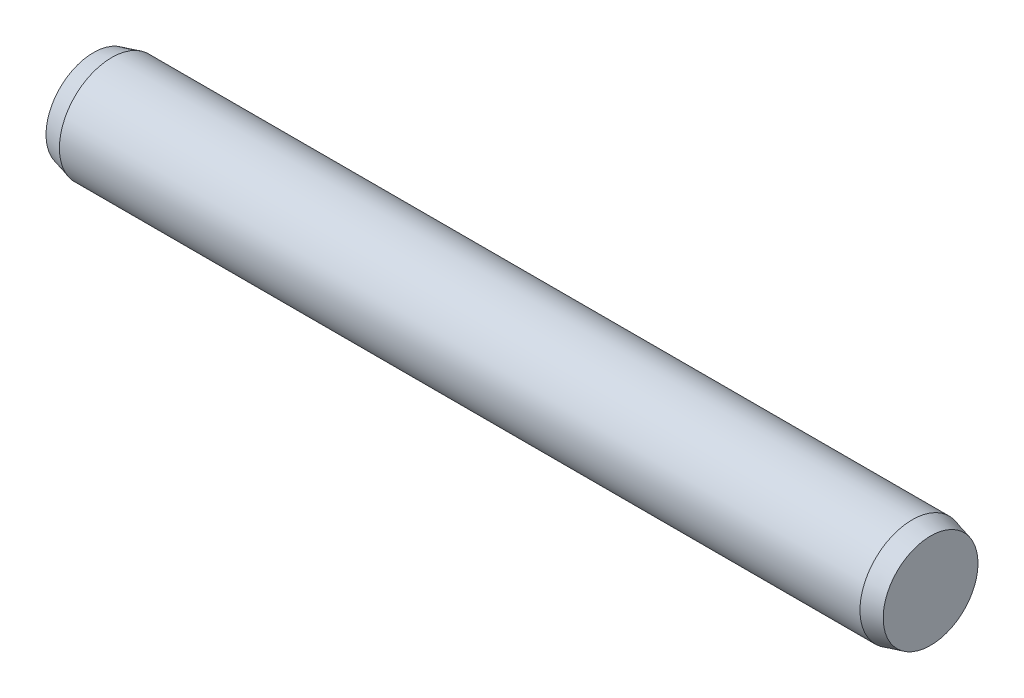
SolidWorks part; units mm, degrees
ref_plane "Front Plane" through (0, 0, 0) normal (0, 0, 1) x (1, 0, 0)
ref_plane "Top Plane" through (0, 0, 0) normal (0, 1, 0) x (1, 0, 0)
ref_plane "Right Plane" through (0, 0, 0) normal (1, 0, 0) x (0, 0, -1)
sketch "Sketch1" plane through (0, 0, 0) normal (0, 0, 1) x (1, 0, 0)
  line L0 (-7.65, 0) -> (7.65, 0) construction
  line L1 (7.65, 1) -> (7.65, -1) construction
  line L2 (-7.65, 1) -> (-7.65, -1) construction
  line L3 (8, 1) -> (8, -1) construction
  line L4 (-8, 1) -> (-8, -1) construction
  line L5 (-7.65, 0) -> (-8, 0) construction
  line L6 (7.65, 0) -> (8, 0) construction
  dimension "D1" = 0.35
  dimension "Dia" = 2
  dimension "Length" = 16
  dimension "C" = 0.35
sketch "Sketch2" plane through (0, 0, 0) normal (1, 0, 0) x (0, 0, -1)
  circle A0 centre (0, 0) radius 1
extrude "Extrude1" add sketch "Sketch2" against normal up to vertex (7.65 mm away) and the other way up to vertex (7.65 mm away) up to point (-7.65, 1, 0) other way up to point (7.65, 1, 0)
sketch "Sketch3" plane through (7.65, 0, 0) normal (1, 0, 0) x (0, 0, -1)
  circle A1 centre (0, 0) radius 1
  circle A2 centre (0, 0) radius 1
  dimension "D1" = 0
extrude "Extrude2" add sketch "Sketch3" along normal up to vertex (0.35 mm away) draft 15 up to point (8, 0, 0)
sketch "Sketch4" plane through (-7.65, 0, 0) normal (-1, 0, 0) x (0, 0, 1)
  circle A1 centre (0, 0) radius 1
  circle A2 centre (0, 0) radius 1
  dimension "D1" = 0
extrude "Extrude3" add sketch "Sketch4" along normal up to vertex (0.35 mm away) draft 15 up to point (-8, 0, 0)
equation "\"D1@Sketch1\" = \"C@Sketch1\""
